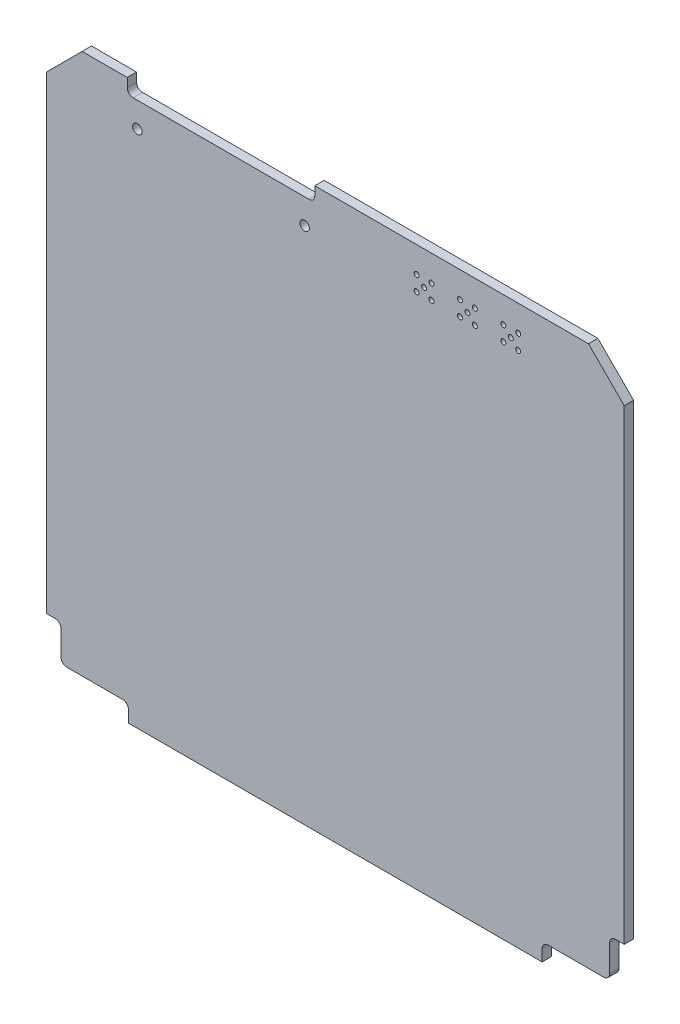
SolidWorks part; units mm, degrees
ref_plane "Front Plane" through (0, 0, 0) normal (0, 0, 1) x (1, 0, 0)
ref_plane "Top Plane" through (0, 0, 0) normal (0, 1, 0) x (1, 0, 0)
ref_plane "Right Plane" through (0, 0, 0) normal (1, 0, 0) x (0, 0, -1)
ref_plane "Plane1" through (0, 0, -0.0125) normal (0, 0, -1) x (-1, 0, 0)
sketch "Sketch1" plane through (0, 0, -0.0125) normal (0, 0, -1) x (-1, 0, 0)
  line L0 (47.8, -40.8) -> (49.3, -40.8)
  line L1 (49.3, -40.8) -> (49.3, 39.2)
  line L2 (49.3, 39.2) -> (43.2, 45.3)
  line L3 (43.2, 45.3) -> (35.5, 45.3)
  line L4 (35.5, 45.3) -> (35.5, 43.8)
  line L5 (34.5, 42.8) -> (4.5, 42.8)
  line L6 (3.5, 43.8) -> (3.5, 45.3)
  line L7 (3.5, 45.3) -> (-43.2, 45.3)
  line L8 (-43.2, 45.3) -> (-49.3, 39.2)
  line L9 (-49.3, 39.2) -> (-49.3, -40.4)
  line L10 (-49.3, -40.4) -> (-47.8, -40.4)
  line L11 (-46.8, -41.4) -> (-46.8, -46)
  line L12 (-45.8, -47) -> (-36.3, -47)
  line L13 (-35.3, -48) -> (-35.3, -50)
  line L14 (-35.3, -50) -> (35.3, -50)
  line L15 (35.3, -50) -> (35.3, -48)
  line L16 (36.3, -47) -> (45.8, -47)
  line L17 (46.8, -46) -> (46.8, -41.8)
  arc A0 (46.8, -41.8) -> (47.8, -40.8) centre (47.8, -41.8) cw
  arc A1 (35.5, 43.8) -> (34.5, 42.8) centre (34.5, 43.8) cw
  arc A2 (4.5, 42.8) -> (3.5, 43.8) centre (4.5, 43.8) cw
  arc A3 (-47.8, -40.4) -> (-46.8, -41.4) centre (-47.8, -41.4) cw
  arc A4 (-46.8, -46) -> (-45.8, -47) centre (-45.8, -46) ccw
  arc A5 (-36.3, -47) -> (-35.3, -48) centre (-36.3, -48) cw
  arc A6 (35.3, -48) -> (36.3, -47) centre (36.3, -48) cw
  arc A7 (45.8, -47) -> (46.8, -46) centre (45.8, -46) ccw
  circle A8 centre (-13.87, 38.33) radius 0.425
  circle A9 centre (-22.54, 39.6) radius 0.425
  circle A10 centre (-23.81, 40.87) radius 0.425
  circle A11 centre (-21.27, 40.87) radius 0.425
  circle A12 centre (-13.87, 40.87) radius 0.425
  circle A13 centre (-31.21, 40.87) radius 0.425
  circle A14 centre (-16.41, 40.87) radius 0.425
  circle A15 centre (-15.14, 39.6) radius 0.425
  circle A16 centre (-29.94, 39.6) radius 0.425
  circle A17 centre (-28.67, 40.87) radius 0.425
  circle A18 centre (-28.67, 38.33) radius 0.425
  circle A19 centre (-16.41, 38.33) radius 0.425
  circle A20 centre (-21.27, 38.33) radius 0.425
  circle A21 centre (-23.81, 38.33) radius 0.425
  circle A22 centre (-31.21, 38.33) radius 0.425
  circle A23 centre (33.775, 38.54) radius 0.8
  circle A24 centre (5.225, 38.54) radius 0.8
extrude "Boss-Extrude1" add sketch "Sketch1" against normal blind 1.6
